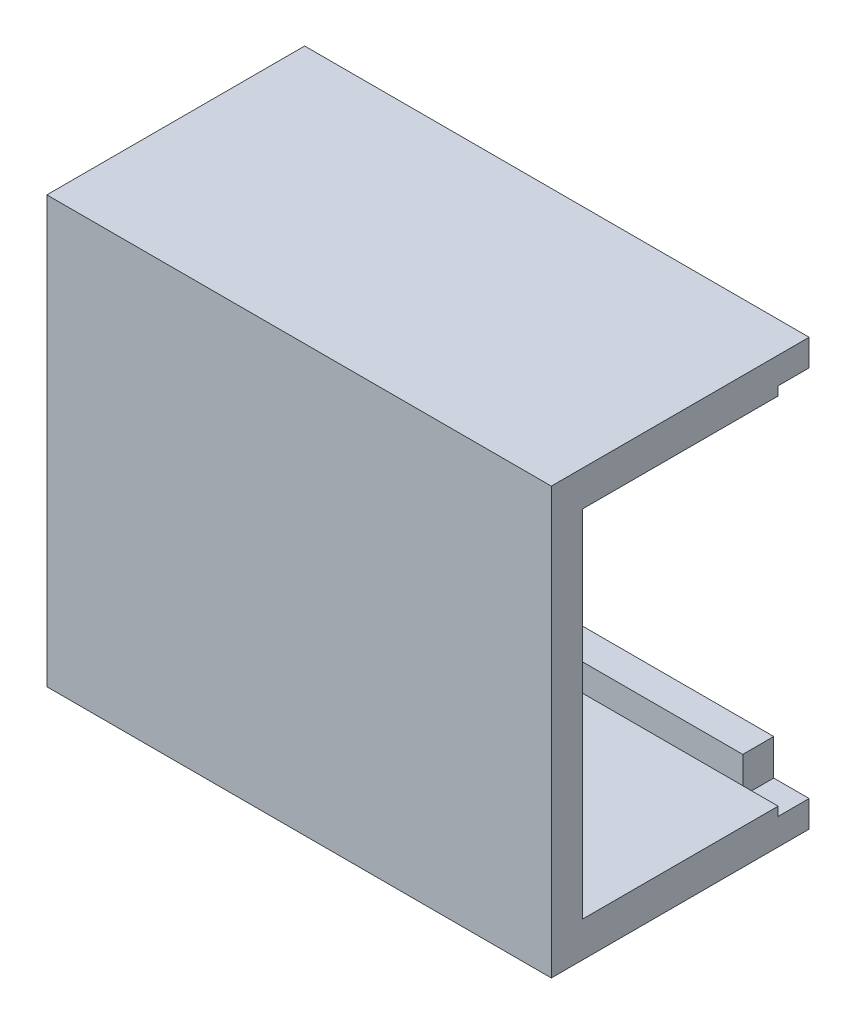
SolidWorks part; units mm, degrees
ref_plane "Front Plane" through (0, 0, 0) normal (1, 0, 0) x (0, 1, 0)
ref_plane "Top Plane" through (0, 0, 0) normal (0, 0, 1) x (0, 1, 0)
ref_plane "Right Plane" through (0, 0, 0) normal (0, 1, 0) x (-1, 0, 0)
sketch "Sketch1" plane through (0, 0, 0) normal (0, 0, 1) x (0, 1, 0)
  line L1 (-12.0332, -14.25) -> (12.0332, -14.25)
  line L2 (-12.0332, -14.25) -> (-12.0332, 14.25)
  line L3 (-12.0332, 14.25) -> (12.0332, 14.25)
  line L4 (12.0332, -14.25) -> (12.0332, 14.25)
  line L5 (-12.0332, -14.25) -> (12.0332, 14.25) construction
  line L6 (-12.0332, 14.25) -> (12.0332, -14.25) construction
  point P0 (0, 0)
  dimension "D1" = 24.0664
  dimension "D2" = 28.5
extrude "Boss-Extrude1" add sketch "Sketch1" along normal blind 14.5651 contours L3 L4 L1 L2
sketch "Sketch2" plane through (14.25, 0, 0) normal (1, 0, 0) x (0, 1, 0)
  line L0 (0, 14.5651) -> (0, 0) construction
  line L1 (-10.0332, 12.8151) -> (10.0332, 12.8151)
  line L2 (-10.0332, 12.8151) -> (-10.0332, 1.75)
  line L3 (-10.0332, 1.75) -> (-8.5, 1.75)
  line L4 (10.0332, 12.8151) -> (10.0332, 1.75)
  line L5 (-12.0332, 14.5651) -> (12.0332, 14.5651) construction
  line L6 (-12.0332, 0) -> (12.0332, 0) construction
  line L7 (12.0332, 7.2826) -> (-12.0332, 7.2826) construction
  line L8 (12.0332, 14.5651) -> (12.0332, 0) construction
  line L9 (-12.0332, 14.5651) -> (-12.0332, 0) construction
  line L10 (-8.5, 1.75) -> (-8.5, 0)
  line L11 (8.5, 1.75) -> (8.5, 0)
  line L12 (8.5, 1.75) -> (10.0332, 1.75)
  line L13 (-8.5, 0) -> (8.5, 0)
  dimension "D1" = 20.0664
  dimension "D2" = 10.0332
  dimension "D3" = 5.5326
  dimension "D4" = 11.0651
  dimension "D5" = 17
  dimension "D6" = 8.5
extrude "Cut-Extrude1" cut sketch "Sketch2" against normal through all
sketch "Sketch4" plane through (14.25, 0, 0) normal (1, 0, 0) x (0, 1, 0)
  line L3 (10.0332, 1.75) -> (10.5332, 1.75)
  line L4 (10.5332, 1.75) -> (10.5332, 0)
  line L5 (8.5, 0) -> (12.0332, 0) construction
  line L11 (-12.0332, 0) -> (-8.5, 0) construction
  line L12 (-10.5332, 0) -> (-10.5332, 1.75)
  line L13 (-10.5332, 1.75) -> (-10.0332, 1.75)
  line L14 (-10.0332, 1.75) -> (-8.5, 1.75)
  line L15 (-8.5, 1.75) -> (-8.5, 0)
  line L16 (-8.5, 0) -> (-10.5332, 0)
  line L17 (10.5332, 0) -> (8.5, 0)
  line L18 (8.5, 0) -> (8.5, 1.75)
  line L19 (8.5, 1.75) -> (10.0332, 1.75)
  dimension "D1" = 0.5
extrude "Cut-Extrude2" cut sketch "Sketch4" against normal blind 2
equation "\"delta\"= 0.03mm"
equation "\"wall\"= 2mm"
equation "\"lip_t\"= 1.5mm"
equation "\"lip_w\"= 2mm"
equation "\"groove_extra\"= 0.5mm"
equation "\"end_gap\"= 0.5mm"
equation "\"W_hole_t\"= 20.0064mm"
equation "\"W_shaft_t\"= 19.9873mm"
equation "\"H_hole_t\"= 11.0051mm"
equation "\"H_shaft_t\"= 10.9898mm"
equation "\"lid_in_w\"= \"W_hole_t\" + 2 * \"delta\""
equation "\"box_w\"= \"W_shaft_t\" - 2 * \"delta\""
equation "\"lid_in_h\"= \"H_hole_t\" + 2 * \"delta\""
equation "\"box_rim_groove\"= \"H_shaft_t\" - 2 * \"delta\""
equation "\"box_h\"= \"box_rim_groove\" + \"lip_t\""
equation "\"cav_w\"= \"box_w\" - 2 * \"wall\""
equation "\"cav_h\" = \"box_h\" - 2 * \"wall\""
equation "\"cav_l\"= 24mm"
equation "\"box_l\"= \"cav_l\" + 2 * \"wall\""
equation "\"groove_w\"= \"lip_w\" + \"groove_extra\""
equation "\"groove_h\"= \"lip_t\""
equation "\"lid_w\"= \"lid_in_w\" + 2 * \"wall\""
equation "\"lid_h\"= \"lid_in_h\" + \"wall\" + \"lip_t\""
equation "\"lid_l\" = \"box_l\" + \"end_gap\""
equation "\"D1@Sketch1\"=\"lid_w\""
equation "\"D2@Sketch1\"=\"lid_l\""
equation "\"D1@Boss-Extrude1\"=\"lid_h\""
equation "\"D1@Sketch2\"=\"lid_in_w\""
equation "\"D2@Sketch2\"=\"lid_in_w\" /2"
equation "\"D3@Sketch2\"=\"lid_in_h\"/2"
equation "\"D4@Sketch2\"=\"lid_in_h\""
